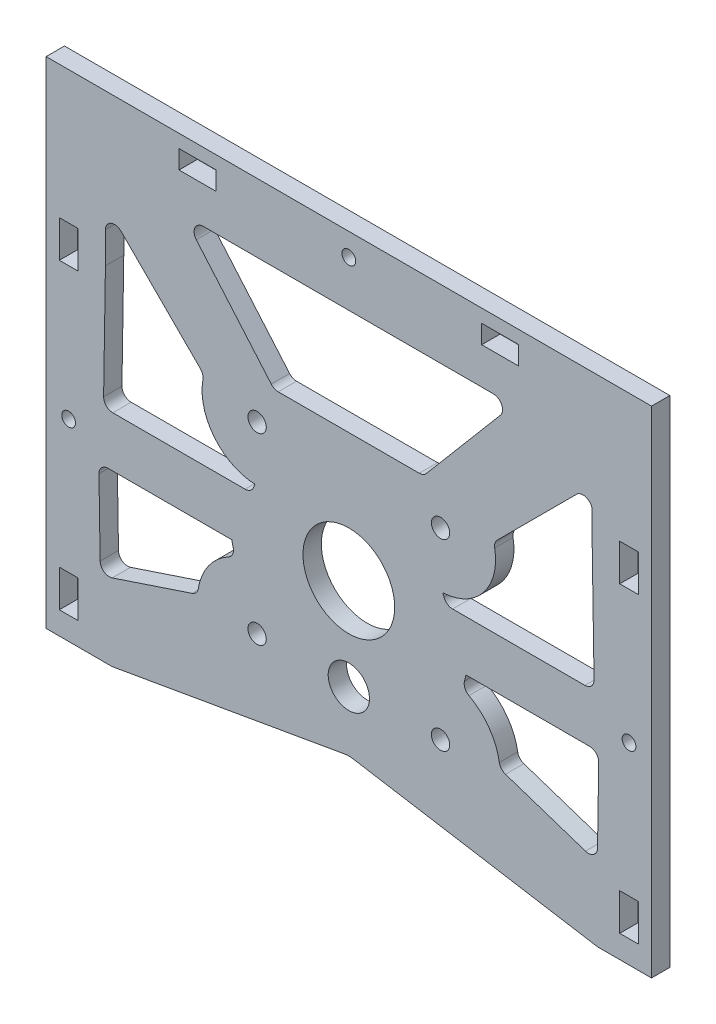
SolidWorks part; units mm, degrees
ref_plane "前视基准面" through (0, 0, 0) normal (0, 0, 1) x (1, 0, 0)
ref_plane "上视基准面" through (0, 0, 0) normal (0, 1, 0) x (1, 0, 0)
ref_plane "右视基准面" through (0, 0, 0) normal (1, 0, 0) x (0, 0, -1)
sketch "草图1" plane through (0, 0, 0) normal (0, 0, 1) x (1, 0, 0)
  line L261 (47.0274, 35.0547) -> (47.0274, 15.0547) construction
  line L315 (47.0274, 15.0547) -> (27.0274, 15.0547) construction
  line L316 (47.0274, 35.0547) -> (47.0274, 101.0547) construction
  line L323 (47.0274, 101.0547) -> (113.0274, 101.0547)
  line L328 (113.0274, 101.0547) -> (113.0274, -30.9453)
  line L329 (113.0274, -30.9453) -> (-18.9726, -30.9453)
  line L330 (-18.9726, -30.9453) -> (-18.9726, 101.0547)
  line L331 (-18.9726, 101.0547) -> (47.0274, 101.0547)
  line L332 (47.0274, 96.1552) -> (80.0274, 96.1552) construction
  line L333 (18.0524, 98.1802) -> (18.0524, 94.1302)
  line L334 (76.0024, 98.1802) -> (84.0524, 98.1802)
  line L335 (76.0024, 98.1802) -> (76.0024, 94.1302)
  line L336 (76.0024, 94.1302) -> (84.0524, 94.1302)
  line L337 (84.0524, 98.1802) -> (84.0524, 94.1302)
  line L338 (76.0024, 98.1802) -> (84.0524, 94.1302) construction
  line L339 (76.0024, 94.1302) -> (84.0524, 98.1802) construction
  line L340 (10.0024, 98.1802) -> (10.0024, 94.1302)
  line L341 (18.0524, 94.1302) -> (10.0024, 94.1302)
  line L342 (18.0524, 98.1802) -> (10.0024, 98.1802)
  line L343 (110.1529, 64.0297) -> (110.1529, 72.0797)
  line L344 (110.1529, 72.0797) -> (106.1029, 72.0797)
  line L345 (106.1029, 64.0297) -> (106.1029, 72.0797)
  line L346 (110.1529, 64.0297) -> (106.1029, 64.0297)
  line L355 (106.1029, 6.0797) -> (106.1029, -1.9703)
  line L360 (110.1529, -1.9703) -> (106.1029, -1.9703)
  line L361 (110.1529, 6.0797) -> (110.1529, -1.9703)
  line L362 (110.1529, 6.0797) -> (106.1029, 6.0797)
  line L363 (76.0024, -28.0708) -> (84.0524, -28.0708)
  line L364 (84.0524, -28.0708) -> (84.0524, -24.0208)
  line L366 (76.0024, -24.0208) -> (84.0524, -24.0208)
  line L367 (76.0024, -28.0708) -> (76.0024, -24.0208)
  line L377 (18.0524, -24.0208) -> (10.0024, -24.0208)
  line L378 (10.0024, -28.0708) -> (10.0024, -24.0208)
  line L379 (18.0524, -28.0708) -> (10.0024, -28.0708)
  line L380 (18.0524, -28.0708) -> (18.0524, -24.0208)
  line L381 (-16.0981, 6.0797) -> (-16.0981, -1.9703)
  line L382 (-16.0981, -1.9703) -> (-12.0481, -1.9703)
  line L383 (-12.0481, 6.0797) -> (-12.0481, -1.9703)
  line L384 (-16.0981, 6.0797) -> (-12.0481, 6.0797)
  line L385 (-12.0481, 64.0297) -> (-12.0481, 72.0797)
  line L386 (-16.0981, 72.0797) -> (-12.0481, 72.0797)
  line L387 (-16.0981, 64.0297) -> (-16.0981, 72.0797)
  line L388 (-16.0981, 64.0297) -> (-12.0481, 64.0297)
  circle A39 centre (47.0274, 96.1552) radius 1.5
  circle A40 centre (108.1279, 35.0547) radius 1.5
  circle A41 centre (47.0274, 35.0547) radius 10
  circle A42 centre (47.0274, 15.0547) radius 4.5
  circle A43 centre (27.0274, 15.0547) radius 2
  circle A44 centre (27.0274, 55.0547) radius 2
  circle A45 centre (67.0274, 55.0547) radius 2
  circle A46 centre (67.0274, 15.0547) radius 2
  circle A47 centre (47.0274, -26.0458) radius 1.5
  circle A48 centre (-14.0731, 35.0547) radius 1.5
  point P5 (210.9534, 218.4629)
  point P6 (288.6284, 218.4629)
extrude "凸台-拉伸1" add sketch "草图1" along normal blind 4 contours L331 L323 L328 L329 L330
sketch "草图2" plane through (0, 0, 0) normal (0, 0, -1) x (-1, 0, 0)
  line L0 (-113.0274, -30.9453) -> (-113.0274, 101.0547) construction
  line L1 (18.9726, -30.9453) -> (-113.0274, -30.9453)
  line L2 (18.9726, -30.9453) -> (18.9726, -6.9453)
  line L3 (18.9726, -6.9453) -> (-113.0274, -6.9453)
  line L4 (-113.0274, -30.9453) -> (-113.0274, -6.9453)
extrude "切除-拉伸1" cut sketch "草图2" against normal blind 4
sketch "草图3" plane through (0, 0, 0) normal (0, 0, -1) x (-1, 0, 0)
  line L4 (-72.5421, 30.0547) -> (-99.5157, 30.0547)
  line L5 (-101.2554, 11.6782) -> (-101.5154, 28.0229)
  line L6 (-81.194, 15.6111) -> (-98.6243, 9.8122)
  line L7 (-47.0274, 35.0547) -> (-47.0274, 28.724) construction
  line L8 (-12.8609, 15.6111) -> (4.5694, 9.8122)
  line L9 (7.2005, 11.6782) -> (7.4606, 28.0229)
  line L10 (-21.5127, 30.0547) -> (5.4608, 30.0547)
  line L11 (4.5694, -6.9453) -> (-101.2554, -6.9453)
  line L12 (18.9726, -6.9453) -> (-113.0274, -6.9453) construction
  line L13 (-101.2554, -6.9453) -> (-47.8669, 1.9154)
  line L14 (-46.1891, 1.9085) -> (4.5694, -6.9453)
  line L17 (12.0481, 64.0297) -> (12.0481, 72.0797) construction
  line L18 (-24.4, 41.0547) -> (4.4448, 41.0547)
  line L20 (12.0481, 68.0547) -> (12.0481, 94.1302) construction
  line L21 (6.4445, 43.0866) -> (6.0481, 68.007)
  line L22 (6.0481, 68.007) -> (6.0481, 74.8165)
  line L23 (2.6339, 76.2307) -> (-14.6607, 58.9361)
  line L24 (-26.5374, 43.0647) -> (-26.5374, 43.0647)
  line L25 (12.0481, 94.1302) -> (-22.7848, 59.2974) construction
  line L26 (12.5731, 35.0547) -> (12.0481, 68.0547) construction
  line L27 (-31.0274, 35.0547) -> (12.5731, 35.0547) construction
  line L28 (-31.2701, 50.8121) -> (-35.7137, 46.3684) construction
  line L29 (6.0481, 79.645) -> (-15.4363, 58.1606) construction
  line L30 (6.0481, 68.007) -> (6.0481, 79.645) construction
  line L31 (-25.8614, 41.0547) -> (6.4769, 41.0547) construction
  line L32 (6.4769, 41.0547) -> (6.0481, 68.007) construction
  line L33 (-100.1029, 68.007) -> (-100.1029, 74.8165)
  line L34 (-96.6887, 76.2307) -> (-79.3941, 58.9361)
  line L35 (-69.6548, 41.0547) -> (-98.4996, 41.0547)
  line L36 (-100.4994, 43.0866) -> (-100.1029, 68.007)
  line L41 (-13.7697, 82.8291) -> (-30.1098, 63.7536)
  line L42 (-31.6287, 63.0547) -> (-62.3905, 63.0547)
  line L43 (-63.917, 63.7626) -> (-80.0635, 82.8381)
  line L44 (-78.537, 86.1302) -> (-15.2887, 86.1302)
  arc A5 (-73.2304, 26.4794) -> (-79.8523, 17.1816) centre (-67.0274, 15.0547) ccw
  arc A6 (-72.2449, 28.724) -> (-72.5421, 30.0547) centre (-47.0274, 35.0547) cw
  arc A7 (-73.2304, 26.4794) -> (-72.2449, 28.724) centre (-74.1847, 28.237) ccw
  arc A8 (-99.5157, 30.0547) -> (-101.5154, 28.0229) centre (-99.5157, 28.0547) ccw
  arc A9 (-101.2554, 11.6782) -> (-98.6243, 9.8122) centre (-99.2556, 11.71) ccw
  arc A10 (-81.194, 15.6111) -> (-79.8523, 17.1816) centre (-81.8253, 17.5089) ccw
  arc A11 (-21.8099, 28.724) -> (-21.5127, 30.0547) centre (-47.0274, 35.0547) ccw
  arc A12 (5.4608, 30.0547) -> (7.4606, 28.0229) centre (5.4608, 28.0547) cw
  arc A13 (-20.8244, 26.4794) -> (-21.8099, 28.724) centre (-19.8701, 28.237) cw
  arc A14 (-12.8609, 15.6111) -> (-14.2026, 17.1816) centre (-12.2295, 17.5089) cw
  arc A15 (7.2005, 11.6782) -> (4.5694, 9.8122) centre (5.2008, 11.71) cw
  arc A16 (-20.8244, 26.4794) -> (-14.2026, 17.1816) centre (-27.0274, 15.0547) cw
  arc A21 (-15.2152, 57.1695) -> (-26.5374, 43.0647) centre (-27.0274, 55.0547) cw
  arc A22 (-26.5374, 43.0647) -> (-26.2856, 42.3881) centre (-47.0274, 35.0547) cw
  arc A23 (-35.7137, 46.3684) -> (-31.0274, 35.0547) centre (-47.0274, 35.0547) cw construction
  arc A24 (-22.7848, 59.2974) -> (-31.2701, 50.8121) centre (-27.0274, 55.0547) cw construction
  arc A25 (-15.4363, 58.1606) -> (-26.5374, 43.0647) centre (-27.0274, 55.0547) cw construction
  arc A26 (-15.2152, 57.1695) -> (-14.6607, 58.9361) centre (-13.2465, 57.5219) cw
  arc A27 (2.6339, 76.2307) -> (6.0481, 74.8165) centre (4.0481, 74.8165) cw
  arc A28 (4.4448, 41.0547) -> (6.4445, 43.0866) centre (4.4448, 43.0547) ccw
  arc A29 (-26.5374, 43.0647) -> (-25.8614, 41.0547) centre (-47.0274, 35.0547) cw construction
  arc A30 (-26.2856, 42.3881) -> (-24.4, 41.0547) centre (-24.4, 43.0547) ccw
  arc A31 (-67.5174, 43.0647) -> (-67.7692, 42.3881) centre (-47.0274, 35.0547) ccw
  arc A32 (-78.8396, 57.1695) -> (-79.3941, 58.9361) centre (-80.8083, 57.5219) ccw
  arc A33 (-67.7692, 42.3881) -> (-69.6548, 41.0547) centre (-69.6548, 43.0547) cw
  arc A34 (-98.4996, 41.0547) -> (-100.4994, 43.0866) centre (-98.4996, 43.0547) cw
  arc A35 (-96.6887, 76.2307) -> (-100.1029, 74.8165) centre (-98.1029, 74.8165) ccw
  arc A36 (-78.8396, 57.1695) -> (-67.5174, 43.0647) centre (-67.0274, 55.0547) ccw
  arc A37 (-47.8669, 1.9154) -> (-46.1891, 1.9085) centre (-47.0483, -3.0171) cw
  arc A38 (-31.6287, 63.0547) -> (-30.1098, 63.7536) centre (-31.6287, 65.0547) ccw
  arc A39 (-63.917, 63.7626) -> (-62.3905, 63.0547) centre (-62.3905, 65.0547) ccw
  arc A40 (-80.0635, 82.8381) -> (-78.537, 86.1302) centre (-78.537, 84.1302) cw
  arc A41 (-15.2887, 86.1302) -> (-13.7697, 82.8291) centre (-15.2887, 84.1302) cw
  dimension "D1" = 2
  dimension "D2" = 6
  dimension "D3" = 2
  dimension "D4" = 2
  dimension "D5" = 5
  dimension "D6" = 2
extrude "切除-拉伸2" cut sketch "草图3" against normal blind 4
